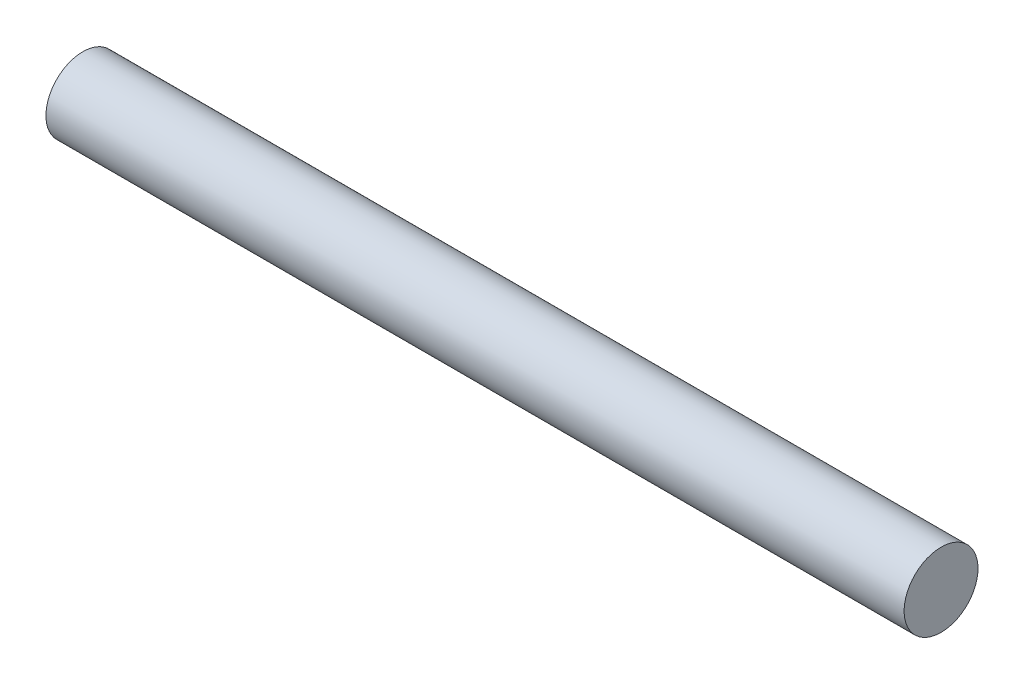
SolidWorks part; units mm, degrees
ref_plane "Front Plane" through (0, 0, 0) normal (1, 0, 0) x (0, 1, 0)
ref_plane "Top Plane" through (0, 0, 0) normal (0, 0, 1) x (0, 1, 0)
ref_plane "Right Plane" through (0, 0, 0) normal (0, 1, 0) x (-1, 0, 0)
sketch "Sketch1" plane through (0, 0, 0) normal (1, 0, 0) x (0, 1, 0)
  circle A0 centre (0, 0) radius 9.9
  dimension "D1" = 19.8
extrude "Boss-Extrude2" add sketch "Sketch1" along normal blind 230
